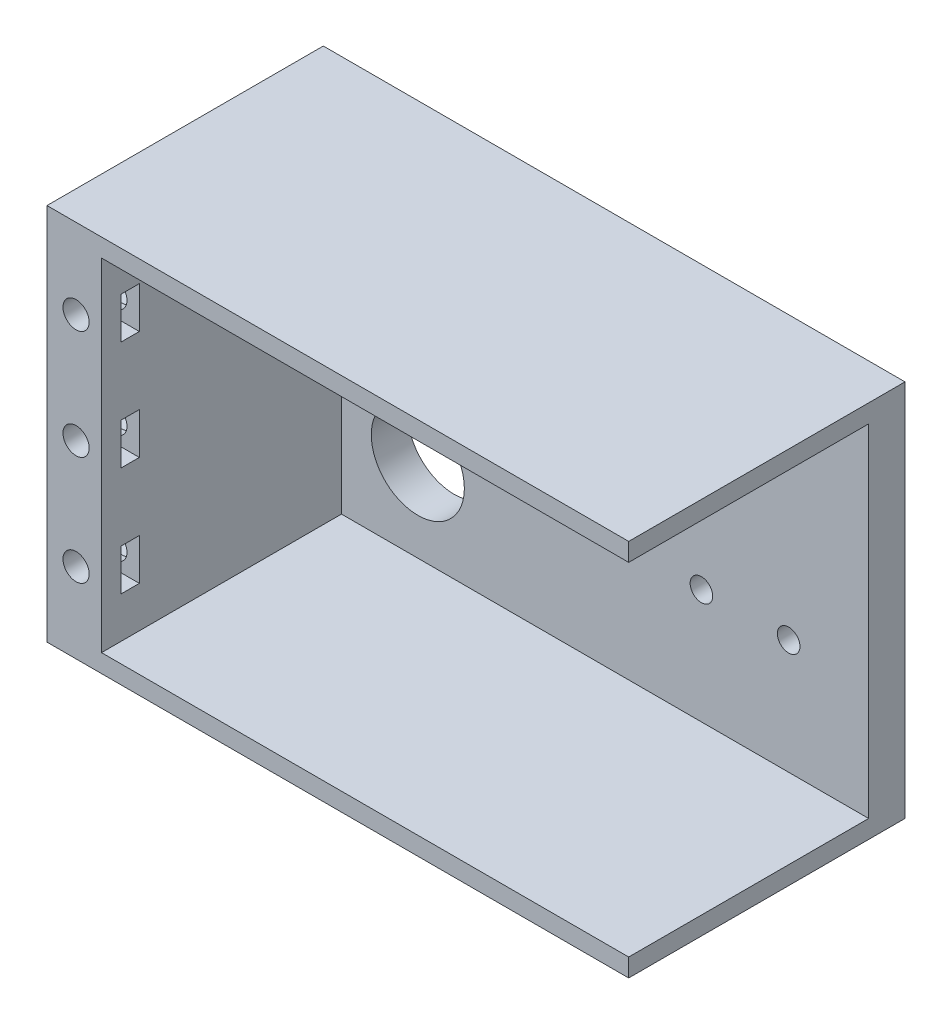
SolidWorks part; units mm, degrees
material "ABS"
ref_plane "Plan de face" through (0, 0, 0) normal (0, 0, 1) x (1, 0, 0)
ref_plane "Plan de dessus" through (0, 0, 0) normal (0, 1, 0) x (1, 0, 0)
ref_plane "Plan de droite" through (0, 0, 0) normal (1, 0, 0) x (0, 0, -1)
sketch "Esquisse3" plane through (0, 0, 0) normal (0, 0, 1) x (1, 0, 0)
  line L1 (-40, -26) -> (40, -26)
  line L2 (-40, -26) -> (-40, 26)
  line L3 (-40, 26) -> (40, 26)
  line L4 (40, -26) -> (40, 26)
  line L5 (-40, -26) -> (40, 26) construction
  line L6 (-40, 26) -> (40, -26) construction
  point P0 (0, 0)
  dimension "D1" = 80
  dimension "D2" = 52
extrude "Boss.-Extru.1" add sketch "Esquisse3" along normal blind 5 contours L3 L4 L1 L2
sketch "Esquisse4" plane through (0, 0, 5) normal (0, 0, 1) x (1, 0, 0)
  line L0 (-40, -26) -> (40, -26) construction
  line L1 (-40, -26) -> (-40, 26) construction
  circle A0 centre (-22, -12) radius 6.4
  dimension "D1" = 12.8
  dimension "D2" = 14
  dimension "D3" = 18
extrude "Enlèv. mat.-Extru.1" cut sketch "Esquisse4" against normal blind 10 contours A0
sketch "Esquisse5" plane through (0, 0, 5) normal (0, 0, 1) x (1, 0, 0)
  line L0 (40, -26) -> (40, 26) construction
  line L1 (-40, -26) -> (40, -26)
  line L3 (-32.5, -23.5) -> (40, -23.5)
  line L4 (40, -26) -> (40, -23.5)
  line L7 (-40, 26) -> (-40, -26)
  line L9 (-32.5, 23.5) -> (-32.5, -23.5)
  line L10 (-40, 26) -> (40, 26)
  line L12 (-32.5, 23.5) -> (40, 23.5)
  line L13 (40, 26) -> (40, 23.5)
  dimension "D1" = 7.5
  dimension "D2" = 2.5
  dimension "D3" = 2.5
extrude "Boss.-Extru.2" add sketch "Esquisse5" along normal blind 33
hole_wizard "Chambrage pour vis à tête ronde bombée M2.51" positions "Esquisse9" profile "Esquisse10" counterbore size "M2.5" standard "Ansi Metric" end condition up to next
sketch "Esquisse9" plane through (0, 0, 0) normal (0, 0, -1) x (-1, 0, 0)
  line L0 (40, 26) -> (-40, 26) construction
  line L1 (-40, -26) -> (-40, 26) construction
  point P0 (-17, 16.25)
  dimension "D1" = 9.75
  dimension "D2" = 23
sketch "Esquisse10" plane through (17, 16.25, 0) normal (1, 0, 0) x (0, 1, 0)
  line L0 (0, 0) -> (0, 5)
  line L1 (0, 5) -> (1.55, 5)
  line L3 (1.55, 5) -> (1.55, 2.1)
  line L4 (1.55, 2.1) -> (3, 2.1)
  line L5 (3, 2.1) -> (3, 0)
  line L7 (3, 0) -> (0, 0)
  line L11 (0, -6.35) -> (0, 107.95) construction
  dimension "Diamètre du perçage jusqu'au prochain" = 3.1
  dimension "Profondeur du perçage jusqu'au prochain" = 5
  dimension "Diamètre du chambrage" = 6
  dimension "Profondeur du chambrage" = 2.1
pattern_linear "Répétition linéaire1" count 2 spacing 12 along (1, 0, 0) count 2 spacing 24 along (0, -1, 0) of "Chambrage pour vis à tête ronde bombée M2.51"
sketch "Esquisse11" plane through (-40, 0, 0) normal (-1, 0, 0) x (0, 0, 1)
  line L0 (38, 26) -> (38, -26) construction
  line L1 (35.3, 17.85) -> (32.8, 17.85)
  line L2 (35.3, 17.85) -> (35.3, 12.15)
  line L3 (35.3, 12.15) -> (32.8, 12.15)
  line L4 (32.8, 17.85) -> (32.8, 12.15)
  line L14 (36.4917, 15) -> (30.8768, 15) construction
  line L15 (38, 26) -> (0, 26) construction
  dimension "D1" = 2.7
  dimension "D2" = 2.5
  dimension "D3" = 5.7
  dimension "D4" = 11
  dimension "D5" = 2.85
extrude "Enlèv. mat.-Extru.2" cut sketch "Esquisse11" against normal up to next
pattern_linear "Répétition linéaire2" count 3 spacing 15 along (0, -1, 0) of "Enlèv. mat.-Extru.2"
hole_wizard "Dégagement M31" positions "Esquisse13" profile "Esquisse15" hole size "M3" standard "Ansi Metric"
sketch "Esquisse13" plane through (0, 0, 38) normal (0, 0, 1) x (1, 0, 0)
  point P0 (-36, 15)
sketch "Esquisse15" plane through (-36, 15, 38) normal (1, 0, 0) x (0, -1, 0)
  line L0 (0, 0) -> (0, 7.4315)
  line L1 (0, 7.4315) -> (1.8, 6.35)
  line L2 (1.8, 6.35) -> (1.8, 0)
  line L5 (1.8, 0) -> (0, 0)
  line L10 (0, 7.4315) -> (-1.8, 6.35) construction
  line L11 (0, -6.35) -> (0, 107.95) construction
  dimension "Diamètre du perçage" = 3.6
  dimension "Profondeur du perçage" = 6.35
  dimension "Angle de pointe" = 118
pattern_linear "Répétition linéaire3" count 3 spacing 15 along (0, -1, 0) of "Dégagement M31"
